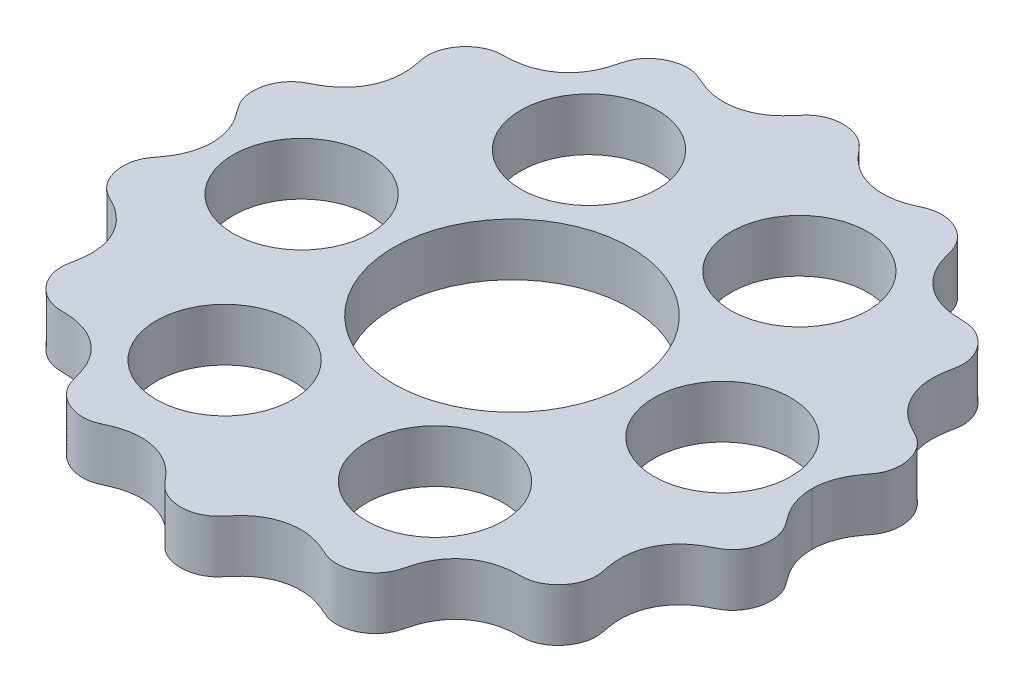
SolidWorks part; units mm, degrees
ref_plane "Front Plane" through (0, 0, 0) normal (0, 0, 1) x (1, 0, 0)
ref_plane "Top Plane" through (0, 0, 0) normal (0, 1, 0) x (1, 0, 0)
ref_plane "Right Plane" through (0, 0, 0) normal (1, 0, 0) x (0, 0, -1)
sketch "Sketch4" plane through (0, 0, 0) normal (0, 1, 0) x (1, 0, 0)
  line L0 (-46.2984, 0) -> (47.8521, 0) construction
  circle A3 centre (0, 0) radius 25.4 construction
  circle A4 centre (-25.4, 0) radius 8.255
  circle A5 centre (-12.7, 21.997) radius 8.255
  circle A6 centre (12.7, 21.997) radius 8.255
  circle A7 centre (25.4, 0) radius 8.255
  circle A8 centre (12.7, -21.997) radius 8.255
  circle A9 centre (-12.7, -21.997) radius 8.255
  circle A10 centre (0, 0) radius 14.2875
  spline S0 degree 4 poles (32.4835, 15.9837) (32.5953, 15.723) (32.847, 15.2136) (33.3061, 14.4926) (34.0639, 13.6417) (34.7997, 13.0364) (35.4402, 12.6188) (35.9434, 12.334) (36.2903, 12.15) (36.6388, 11.9693) (36.9826, 11.7795) (37.3117, 11.5644) (37.6183, 11.3181) (37.9303, 11.0122) (38.2354, 10.6403) (38.5194, 10.1989) (38.7669, 9.6869) (38.9218, 9.2393) (39.013, 8.8722) (39.0636, 8.5935) (39.0902, 8.4068) (39.1095, 8.2195) (39.1215, 8.0305) (39.1257, 7.8669) (39.1247, 7.7269) (39.12, 7.6035) (39.1142, 7.5024) (39.1056, 7.388) (39.0943, 7.28) (39.069, 7.0862) (39.0367, 6.9106) (38.9956, 6.7273) (38.9467, 6.5466) (38.8755, 6.324) (38.774, 6.0623) (38.6319, 5.767) (38.439, 5.4462) (38.2506, 5.1785) (38.0837, 4.9532) (37.8768, 4.6751) (37.6334, 4.3417) (37.3399, 3.9052) (37.0217, 3.3508) (36.6807, 2.6281) (36.372, 1.7183) (36.1807, 0.6558) (36.1759, -0.5393) (36.3608, -1.6747) (36.7048, -2.7257) (37.1593, -3.6326) (37.6153, -4.3245) (38.0005, -4.8413) (38.3307, -5.2853) (38.6375, -5.7474) (38.9451, -6.4219) (39.1444, -7.3268) (39.1477, -8.3428) (38.9072, -9.4197) (38.477, -10.3303) (37.9264, -11.0538) (37.3798, -11.5295) (36.923, -11.8162) (36.5274, -12.027) (36.2092, -12.1927) (35.7324, -12.448) (35.1108, -12.819) (34.3804, -13.3592) (33.6053, -14.1283) (32.9488, -15.0154) (32.4339, -16.0048) (32.0793, -17.0745) (31.8979, -18.1982) (31.8923, -19.1483) (31.9707, -19.9048) (32.0639, -20.4698) (32.1361, -20.849) (32.2289, -21.3217) (32.3166, -21.8949) (32.3074, -22.6656) (32.0867, -23.5999) (31.6293, -24.5418) (30.9167, -25.4221) (30.1003, -26.0591) (29.2549, -26.4633) (28.5251, -26.6346) (27.966, -26.6758) (27.4069, -26.6933) (26.7558, -26.7172) (25.9222, -26.8004) (24.9217, -27.0247) (23.8801, -27.4302) (22.917, -27.992) (22.0571, -28.6968) (21.3206, -29.5254) (20.7222, -30.4546) (20.3435, -31.2925) (20.111, -31.9871) (19.964, -32.5141) (19.8719, -32.865) (19.7553, -33.3028) (19.5836, -33.8202) (19.2473, -34.4715) (18.6656, -35.184) (17.873, -35.8166) (16.877, -36.2983) (15.8919, -36.5268) (14.9775, -36.5425) (14.2617, -36.4056) (13.7514, -36.2222) (13.3383, -36.0423) (13.0085, -35.8961) (12.5082, -35.6824) (11.8253, -35.4294) (10.9409, -35.199) (9.8487, -35.08) (8.7428, -35.1295) (7.6501, -35.3537) (6.5991, -35.7515) (5.6175, -36.3145) (4.8792, -36.9039) (4.3423, -37.4365) (3.9621, -37.8605) (3.7124, -38.1521) (3.4021, -38.5173) (3.0077, -38.9382) (2.3991, -39.4042) (1.5336, -39.8071) (0.5138, -40.0321) (-0.6187, -40.02) (-1.6275, -39.7742) (-2.4733, -39.3581) (-3.0619, -38.887) (-3.442, -38.4706) (-3.8061, -38.0418) (-4.2343, -37.5457) (-4.8255, -36.9453) (-5.6332, -36.3044) (-6.6095, -35.7471) (-7.6556, -35.3525) (-8.7447, -35.1294) (-9.8487, -35.08) (-10.9409, -35.199) (-11.8253, -35.4294) (-12.5082, -35.6824) (-13.0085, -35.8961) (-13.3383, -36.0423) (-13.7514, -36.2222) (-14.2617, -36.4056) (-14.9775, -36.5425) (-15.8919, -36.5268) (-16.877, -36.2983) (-17.873, -35.8166) (-18.6656, -35.184) (-19.2473, -34.4715) (-19.5836, -33.8202) (-19.7553, -33.3028) (-19.8719, -32.865) (-19.964, -32.5141) (-20.111, -31.9871) (-20.3435, -31.2925) (-20.7222, -30.4546) (-21.3206, -29.5254) (-22.0571, -28.6968) (-22.917, -27.992) (-23.8801, -27.4302) (-24.9217, -27.0247) (-25.9222, -26.8004) (-26.7558, -26.7172) (-27.4069, -26.6933) (-27.966, -26.6758) (-28.5251, -26.6346) (-29.2549, -26.4633) (-30.1003, -26.0591) (-30.9167, -25.4221) (-31.6293, -24.5418) (-32.0867, -23.5999) (-32.3074, -22.6656) (-32.3166, -21.8949) (-32.2289, -21.3217) (-32.1361, -20.849) (-32.0639, -20.4698) (-31.9707, -19.9048) (-31.8923, -19.1483) (-31.8979, -18.1982) (-32.0793, -17.0745) (-32.4339, -16.0048) (-32.9488, -15.0154) (-33.6053, -14.1283) (-34.3804, -13.3592) (-35.1108, -12.819) (-35.7324, -12.448) (-36.2092, -12.1927) (-36.5274, -12.027) (-36.923, -11.8162) (-37.3798, -11.5295) (-37.9264, -11.0538) (-38.477, -10.3303) (-38.9072, -9.4197) (-39.1477, -8.3428) (-39.1444, -7.3268) (-38.9451, -6.4219) (-38.6375, -5.7474) (-38.3307, -5.2853) (-38.0005, -4.8413) (-37.6153, -4.3245) (-37.1593, -3.6326) (-36.7048, -2.7257) (-36.3608, -1.6747) (-36.1759, -0.5393) (-36.1807, 0.6558) (-36.372, 1.7183) (-36.6807, 2.6281) (-37.0217, 3.3508) (-37.3399, 3.9052) (-37.6594, 4.3806) (-37.96, 4.7879) (-38.2237, 5.1403) (-38.439, 5.4462) (-38.6319, 5.767) (-38.774, 6.0623) (-38.8755, 6.324) (-38.9467, 6.5466) (-38.9956, 6.7273) (-39.0367, 6.9106) (-39.069, 7.0862) (-39.0943, 7.28) (-39.1056, 7.388) (-39.1142, 7.5024) (-39.12, 7.6035) (-39.1247, 7.7269) (-39.1257, 7.8669) (-39.1215, 8.0305) (-39.1095, 8.2195) (-39.0902, 8.4068) (-39.0536, 8.6637) (-38.9976, 8.9416) (-38.8994, 9.3068) (-38.736, 9.7509) (-38.5194, 10.1989) (-38.2354, 10.6403) (-37.9303, 11.0122) (-37.6183, 11.3181) (-37.3117, 11.5644) (-36.9826, 11.7795) (-36.6388, 11.9693) (-36.2903, 12.15) (-35.9434, 12.334) (-35.4402, 12.6188) (-34.7997, 13.0364) (-34.0639, 13.6417) (-33.3061, 14.4926) (-32.847, 15.2136) (-32.5953, 15.723) (-32.4835, 15.9837) knots 0 0 0 0 0 0.006536 0.013073 0.019609 0.026146 0.028407 0.030669 0.03293 0.035192 0.037454 0.039715 0.041977 0.044239 0.047507 0.050774 0.054042 0.05731 0.058396 0.059482 0.060567 0.061653 0.062739 0.063825 0.064368 0.064911 0.065453 0.065996 0.067073 0.06815 0.069227 0.070304 0.071381 0.072458 0.074612 0.076766 0.07892 0.081074 0.082151 0.083228 0.086907 0.090585 0.094264 0.097942 0.1053 0.112657 0.119003 0.125349 0.131696 0.138042 0.142293 0.144419 0.146545 0.150796 0.155048 0.161391 0.167735 0.174002 0.18027 0.184402 0.188534 0.1906 0.192666 0.194732 0.196799 0.203065 0.209332 0.215598 0.221865 0.228394 0.234924 0.241453 0.247983 0.250205 0.252427 0.254649 0.256871 0.261315 0.265759 0.272285 0.278811 0.285223 0.291636 0.295934 0.300233 0.302382 0.304531 0.308829 0.315243 0.321656 0.32807 0.334483 0.340825 0.347168 0.35351 0.359852 0.361941 0.36403 0.366119 0.368208 0.372386 0.376564 0.382904 0.389245 0.395549 0.401852 0.406007 0.410162 0.41224 0.414317 0.416395 0.418472 0.424777 0.431081 0.437386 0.443691 0.450183 0.456676 0.463168 0.46966 0.471871 0.474081 0.476291 0.478501 0.482922 0.487342 0.493832 0.500321 0.50677 0.513219 0.517542 0.521865 0.524026 0.526188 0.530511 0.536961 0.54341 0.54986 0.556309 0.562614 0.568919 0.575223 0.581528 0.583605 0.585683 0.58776 0.589838 0.593993 0.598148 0.604451 0.610755 0.617096 0.623436 0.627614 0.631792 0.633881 0.63597 0.638059 0.640148 0.64649 0.652832 0.659175 0.665517 0.67193 0.678344 0.684757 0.691171 0.695469 0.697618 0.699767 0.704066 0.708364 0.714777 0.721189 0.727715 0.734241 0.738685 0.743129 0.745351 0.747573 0.749795 0.752017 0.758547 0.765076 0.771606 0.778135 0.784402 0.790668 0.796935 0.803201 0.805268 0.807334 0.8094 0.811466 0.815598 0.81973 0.825998 0.832265 0.838609 0.844952 0.849204 0.853455 0.855581 0.857707 0.861958 0.868304 0.874651 0.880997 0.887343 0.8947 0.902058 0.905736 0.909415 0.913093 0.916772 0.918926 0.92108 0.923234 0.925388 0.927542 0.928619 0.929696 0.930773 0.93185 0.932927 0.934004 0.934547 0.935089 0.935632 0.936175 0.937261 0.938347 0.939433 0.940518 0.941604 0.944324 0.945958 0.949226 0.952493 0.955761 0.958023 0.960285 0.962546 0.964808 0.96707 0.969331 0.971593 0.973854 0.980391 0.986927 0.993464 1 1 1 1 1 construction
  spline S1 degree 4 poles (36.195, 0) (36.195, -0.2828) (36.2251, -0.8411) (36.3585, -1.6676) (36.7048, -2.7257) (37.1593, -3.6326) (37.6153, -4.3245) (38.0005, -4.8413) (38.3307, -5.2853) (38.6375, -5.7474) (38.9451, -6.4219) (39.1444, -7.3268) (39.1477, -8.3428) (38.9072, -9.4197) (38.477, -10.3303) (37.9264, -11.0538) (37.3798, -11.5295) (36.923, -11.8162) (36.5274, -12.027) (36.2092, -12.1927) (35.7324, -12.448) (35.1108, -12.819) (34.3804, -13.3592) (33.6053, -14.1283) (32.9488, -15.0154) (32.4339, -16.0048) (32.0793, -17.0745) (31.8979, -18.1982) (31.8923, -19.1483) (31.9707, -19.9048) (32.0639, -20.4698) (32.1361, -20.849) (32.2289, -21.3217) (32.3166, -21.8949) (32.3074, -22.6656) (32.0867, -23.5999) (31.6293, -24.5418) (30.9167, -25.4221) (30.1003, -26.0591) (29.2549, -26.4633) (28.5251, -26.6346) (27.966, -26.6758) (27.4069, -26.6933) (26.7558, -26.7172) (25.9222, -26.8004) (24.9217, -27.0247) (23.8801, -27.4302) (22.917, -27.992) (22.0571, -28.6968) (21.3206, -29.5254) (20.7222, -30.4546) (20.3435, -31.2925) (20.111, -31.9871) (19.964, -32.5141) (19.8719, -32.865) (19.7553, -33.3028) (19.5836, -33.8202) (19.2473, -34.4715) (18.6656, -35.184) (17.873, -35.8166) (16.877, -36.2983) (15.8919, -36.5268) (14.9775, -36.5425) (14.2617, -36.4056) (13.7514, -36.2222) (13.3383, -36.0423) (13.0085, -35.8961) (12.5082, -35.6824) (11.8253, -35.4294) (10.9409, -35.199) (9.8487, -35.08) (8.7428, -35.1295) (7.6501, -35.3537) (6.5991, -35.7515) (5.6175, -36.3145) (4.8792, -36.9039) (4.3423, -37.4365) (3.9621, -37.8605) (3.7124, -38.1521) (3.4021, -38.5173) (3.0077, -38.9382) (2.3991, -39.4042) (1.5336, -39.8071) (0.5138, -40.0321) (-0.6187, -40.02) (-1.6275, -39.7742) (-2.4733, -39.3581) (-3.0619, -38.887) (-3.442, -38.4706) (-3.8061, -38.0418) (-4.2343, -37.5457) (-4.8255, -36.9453) (-5.6332, -36.3044) (-6.6095, -35.7471) (-7.6556, -35.3525) (-8.7447, -35.1294) (-9.8487, -35.08) (-10.9409, -35.199) (-11.8253, -35.4294) (-12.5082, -35.6824) (-13.0085, -35.8961) (-13.3383, -36.0423) (-13.7514, -36.2222) (-14.2617, -36.4056) (-14.9775, -36.5425) (-15.8919, -36.5268) (-16.877, -36.2983) (-17.873, -35.8166) (-18.6656, -35.184) (-19.2473, -34.4715) (-19.5836, -33.8202) (-19.7553, -33.3028) (-19.8719, -32.865) (-19.964, -32.5141) (-20.111, -31.9871) (-20.3435, -31.2925) (-20.7222, -30.4546) (-21.3206, -29.5254) (-22.0571, -28.6968) (-22.917, -27.992) (-23.8801, -27.4302) (-24.9217, -27.0247) (-25.9222, -26.8004) (-26.7558, -26.7172) (-27.4069, -26.6933) (-27.966, -26.6758) (-28.5251, -26.6346) (-29.2549, -26.4633) (-30.1003, -26.0591) (-30.9167, -25.4221) (-31.6293, -24.5418) (-32.0867, -23.5999) (-32.3074, -22.6656) (-32.3166, -21.8949) (-32.2289, -21.3217) (-32.1361, -20.849) (-32.0639, -20.4698) (-31.9707, -19.9048) (-31.8923, -19.1483) (-31.8979, -18.1982) (-32.0793, -17.0745) (-32.4339, -16.0048) (-32.9488, -15.0154) (-33.6053, -14.1283) (-34.3804, -13.3592) (-35.1108, -12.819) (-35.7324, -12.448) (-36.2092, -12.1927) (-36.5274, -12.027) (-36.923, -11.8162) (-37.3798, -11.5295) (-37.9264, -11.0538) (-38.477, -10.3303) (-38.9072, -9.4197) (-39.1477, -8.3428) (-39.1444, -7.3268) (-38.9451, -6.4219) (-38.6375, -5.7474) (-38.3307, -5.2853) (-38.0005, -4.8413) (-37.6153, -4.3245) (-37.1593, -3.6326) (-36.7048, -2.7257) (-36.3585, -1.6676) (-36.2251, -0.8411) (-36.195, -0.2828) (-36.195, 0) knots 0.112486 0.112486 0.112486 0.112486 0.112486 0.119003 0.125349 0.131696 0.138042 0.142293 0.144419 0.146545 0.150796 0.155048 0.161391 0.167735 0.174002 0.18027 0.184402 0.188534 0.1906 0.192666 0.194732 0.196799 0.203065 0.209332 0.215598 0.221865 0.228394 0.234924 0.241453 0.247983 0.250205 0.252427 0.254649 0.256871 0.261315 0.265759 0.272285 0.278811 0.285223 0.291636 0.295934 0.300233 0.302382 0.304531 0.308829 0.315243 0.321656 0.32807 0.334483 0.340825 0.347168 0.35351 0.359852 0.361941 0.36403 0.366119 0.368208 0.372386 0.376564 0.382904 0.389245 0.395549 0.401852 0.406007 0.410162 0.41224 0.414317 0.416395 0.418472 0.424777 0.431081 0.437386 0.443691 0.450183 0.456676 0.463168 0.46966 0.471871 0.474081 0.476291 0.478501 0.482922 0.487342 0.493832 0.500321 0.50677 0.513219 0.517542 0.521865 0.524026 0.526188 0.530511 0.536961 0.54341 0.54986 0.556309 0.562614 0.568919 0.575223 0.581528 0.583605 0.585683 0.58776 0.589838 0.593993 0.598148 0.604451 0.610755 0.617096 0.623436 0.627614 0.631792 0.633881 0.63597 0.638059 0.640148 0.64649 0.652832 0.659175 0.665517 0.67193 0.678344 0.684757 0.691171 0.695469 0.697618 0.699767 0.704066 0.708364 0.714777 0.721189 0.727715 0.734241 0.738685 0.743129 0.745351 0.747573 0.749795 0.752017 0.758547 0.765076 0.771606 0.778135 0.784402 0.790668 0.796935 0.803201 0.805268 0.807334 0.8094 0.811466 0.815598 0.81973 0.825998 0.832265 0.838609 0.844952 0.849204 0.853455 0.855581 0.857707 0.861958 0.868304 0.874651 0.880997 0.887514 0.887514 0.887514 0.887514 0.887514
  spline S2 degree 4 poles (36.195, 0) (36.195, 0.2828) (36.2251, 0.8411) (36.3585, 1.6676) (36.7048, 2.7257) (37.1593, 3.6326) (37.6153, 4.3245) (38.0005, 4.8413) (38.3307, 5.2853) (38.6375, 5.7474) (38.9451, 6.4219) (39.1444, 7.3268) (39.1477, 8.3428) (38.9072, 9.4197) (38.477, 10.3303) (37.9264, 11.0538) (37.3798, 11.5295) (36.923, 11.8162) (36.5274, 12.027) (36.2092, 12.1927) (35.7324, 12.448) (35.1108, 12.819) (34.3804, 13.3592) (33.6053, 14.1283) (32.9488, 15.0154) (32.4339, 16.0048) (32.0793, 17.0745) (31.8979, 18.1982) (31.8923, 19.1483) (31.9707, 19.9048) (32.0639, 20.4698) (32.1361, 20.849) (32.2289, 21.3217) (32.3166, 21.8949) (32.3074, 22.6656) (32.0867, 23.5999) (31.6293, 24.5418) (30.9167, 25.4221) (30.1003, 26.0591) (29.2549, 26.4633) (28.5251, 26.6346) (27.966, 26.6758) (27.4069, 26.6933) (26.7558, 26.7172) (25.9222, 26.8004) (24.9217, 27.0247) (23.8801, 27.4302) (22.917, 27.992) (22.0571, 28.6968) (21.3206, 29.5254) (20.7222, 30.4546) (20.3435, 31.2925) (20.111, 31.9871) (19.964, 32.5141) (19.8719, 32.865) (19.7553, 33.3028) (19.5836, 33.8202) (19.2473, 34.4715) (18.6656, 35.184) (17.873, 35.8166) (16.877, 36.2983) (15.8919, 36.5268) (14.9775, 36.5425) (14.2617, 36.4056) (13.7514, 36.2222) (13.3383, 36.0423) (13.0085, 35.8961) (12.5082, 35.6824) (11.8253, 35.4294) (10.9409, 35.199) (9.8487, 35.08) (8.7428, 35.1295) (7.6501, 35.3537) (6.5991, 35.7515) (5.6175, 36.3145) (4.8792, 36.9039) (4.3423, 37.4365) (3.9621, 37.8605) (3.7124, 38.1521) (3.4021, 38.5173) (3.0077, 38.9382) (2.3991, 39.4042) (1.5336, 39.8071) (0.5138, 40.0321) (-0.6187, 40.02) (-1.6275, 39.7742) (-2.4733, 39.3581) (-3.0619, 38.887) (-3.442, 38.4706) (-3.8061, 38.0418) (-4.2343, 37.5457) (-4.8255, 36.9453) (-5.6332, 36.3044) (-6.6095, 35.7471) (-7.6556, 35.3525) (-8.7447, 35.1294) (-9.8487, 35.08) (-10.9409, 35.199) (-11.8253, 35.4294) (-12.5082, 35.6824) (-13.0085, 35.8961) (-13.3383, 36.0423) (-13.7514, 36.2222) (-14.2617, 36.4056) (-14.9775, 36.5425) (-15.8919, 36.5268) (-16.877, 36.2983) (-17.873, 35.8166) (-18.6656, 35.184) (-19.2473, 34.4715) (-19.5836, 33.8202) (-19.7553, 33.3028) (-19.8719, 32.865) (-19.964, 32.5141) (-20.111, 31.9871) (-20.3435, 31.2925) (-20.7222, 30.4546) (-21.3206, 29.5254) (-22.0571, 28.6968) (-22.917, 27.992) (-23.8801, 27.4302) (-24.9217, 27.0247) (-25.9222, 26.8004) (-26.7558, 26.7172) (-27.4069, 26.6933) (-27.966, 26.6758) (-28.5251, 26.6346) (-29.2549, 26.4633) (-30.1003, 26.0591) (-30.9167, 25.4221) (-31.6293, 24.5418) (-32.0867, 23.5999) (-32.3074, 22.6656) (-32.3166, 21.8949) (-32.2289, 21.3217) (-32.1361, 20.849) (-32.0639, 20.4698) (-31.9707, 19.9048) (-31.8923, 19.1483) (-31.8979, 18.1982) (-32.0793, 17.0745) (-32.4339, 16.0048) (-32.9488, 15.0154) (-33.6053, 14.1283) (-34.3804, 13.3592) (-35.1108, 12.819) (-35.7324, 12.448) (-36.2092, 12.1927) (-36.5274, 12.027) (-36.923, 11.8162) (-37.3798, 11.5295) (-37.9264, 11.0538) (-38.477, 10.3303) (-38.9072, 9.4197) (-39.1477, 8.3428) (-39.1444, 7.3268) (-38.9451, 6.4219) (-38.6375, 5.7474) (-38.3307, 5.2853) (-38.0005, 4.8413) (-37.6153, 4.3245) (-37.1593, 3.6326) (-36.7048, 2.7257) (-36.3585, 1.6676) (-36.2251, 0.8411) (-36.195, 0.2828) (-36.195, 0) knots 0.112486 0.112486 0.112486 0.112486 0.112486 0.119003 0.125349 0.131696 0.138042 0.142293 0.144419 0.146545 0.150796 0.155048 0.161391 0.167735 0.174002 0.18027 0.184402 0.188534 0.1906 0.192666 0.194732 0.196799 0.203065 0.209332 0.215598 0.221865 0.228394 0.234924 0.241453 0.247983 0.250205 0.252427 0.254649 0.256871 0.261315 0.265759 0.272285 0.278811 0.285223 0.291636 0.295934 0.300233 0.302382 0.304531 0.308829 0.315243 0.321656 0.32807 0.334483 0.340825 0.347168 0.35351 0.359852 0.361941 0.36403 0.366119 0.368208 0.372386 0.376564 0.382904 0.389245 0.395549 0.401852 0.406007 0.410162 0.41224 0.414317 0.416395 0.418472 0.424777 0.431081 0.437386 0.443691 0.450183 0.456676 0.463168 0.46966 0.471871 0.474081 0.476291 0.478501 0.482922 0.487342 0.493832 0.500321 0.50677 0.513219 0.517542 0.521865 0.524026 0.526188 0.530511 0.536961 0.54341 0.54986 0.556309 0.562614 0.568919 0.575223 0.581528 0.583605 0.585683 0.58776 0.589838 0.593993 0.598148 0.604451 0.610755 0.617096 0.623436 0.627614 0.631792 0.633881 0.63597 0.638059 0.640148 0.64649 0.652832 0.659175 0.665517 0.67193 0.678344 0.684757 0.691171 0.695469 0.697618 0.699767 0.704066 0.708364 0.714777 0.721189 0.727715 0.734241 0.738685 0.743129 0.745351 0.747573 0.749795 0.752017 0.758547 0.765076 0.771606 0.778135 0.784402 0.790668 0.796935 0.803201 0.805268 0.807334 0.8094 0.811466 0.815598 0.81973 0.825998 0.832265 0.838609 0.844952 0.849204 0.853455 0.855581 0.857707 0.861958 0.868304 0.874651 0.880997 0.887514 0.887514 0.887514 0.887514 0.887514
  point P23 (0, 0)
  dimension "D1" = 50.8
  dimension "D2" = 16.51
  dimension "D4" = 28.575
  dimension "D3" = 6
extrude "Boss-Extrude2" add sketch "Sketch4" along normal blind 6.35
equation "\"R\"= 1.75in"
equation "\"E\"= 0.125in"
equation "\"Rr\"= 0.25in"
equation "\"N\"= 10"
